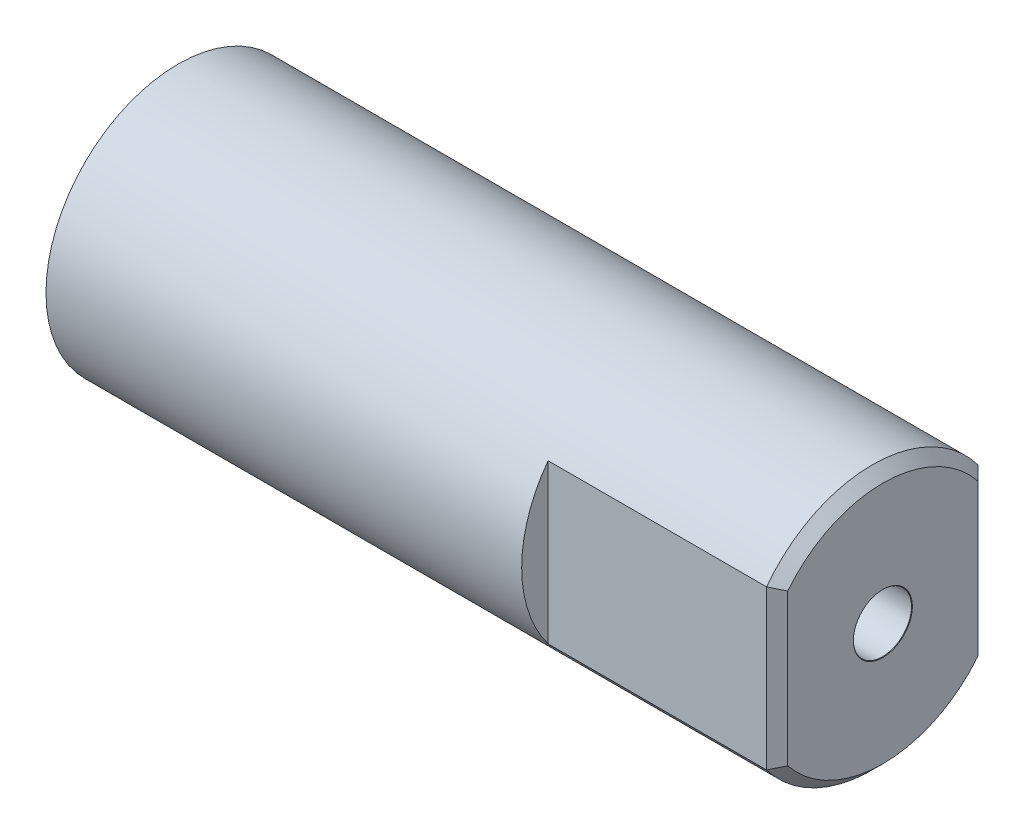
SolidWorks part; units mm, degrees
ref_plane "Front Plane" through (0, 0, 0) normal (0, 0, 1) x (1, 0, 0)
ref_plane "Top Plane" through (0, 0, 0) normal (0, 1, 0) x (1, 0, 0)
ref_plane "Right Plane" through (0, 0, 0) normal (1, 0, 0) x (0, 0, -1)
sketch "Sketch1" plane through (0, 0, 0) normal (0, 0, 1) x (1, 0, 0)
  line L0 (0, 7.5) -> (40, 7.5)
  line L1 (40, 7.5) -> (40, 0)
  line L2 (40, 0) -> (0, 0)
  line L3 (0, 0) -> (0, 7.5)
  dimension "D1" = 7.5
  dimension "D2" = 40
revolve "Revolve1" add sketch "Sketch1" angle 360 about L2
sketch "Sketch4" plane through (40, 0, 0) normal (1, 0, 0) x (0, 0, -1)
  point P0 (0, 0)
hole_wizard "Tap Drill for M4 Tap1" positions "Sketch4" profile "Sketch5" hole size "M4" standard "DIN"
sketch "Sketch5" plane through (40, 0, 0) normal (0, 1, 0) x (0, 0, -1)
  line L0 (0, 0) -> (0, 10.9914)
  line L1 (0, 10.9914) -> (1.65, 10)
  line L2 (1.65, 10) -> (1.65, 0.025)
  line L3 (1.65, 0.025) -> (1.675, 0)
  line L5 (1.675, 0) -> (0, 0)
  line L6 (-1.65, 0.025) -> (-1.675, 0) construction
  line L10 (0, 10.9914) -> (-1.65, 10) construction
  line L11 (0, -6.35) -> (0, 107.95) construction
  dimension "Hole Dia." = 3.3
  dimension "Hole Depth" = 10
  dimension "Near C'Sink Dia." = 3.35
  dimension "Near C'Sink Angle" = 90
  dimension "Drill Angle" = 118
sketch "Sketch6" plane through (40, 0, 0) normal (1, 0, 0) x (0, 0, -1)
  line L1 (-6, 4.5) -> (6, 4.5)
  line L2 (-6, 4.5) -> (-6, -4.5)
  line L3 (-6, -4.5) -> (6, -4.5)
  line L4 (6, 4.5) -> (6, -4.5)
  circle A0 centre (0, 0) radius 7.5 construction
  circle A1 centre (0, 0) radius 7.5
  point P7 (0, 0)
  circle M7 centre (0, 0) radius 7.5
  dimension "D1" = 12
extrude "Cut-Extrude1" cut sketch "Sketch6" against normal blind 13 contours L2 M7 | L4 M7
chamfer "Chamfer1" distance 0.6 angle 45 4 edges at (40, 7.5, 0) (40, -7.5, 0) (40, 0, -6) (40, 0, 6)
